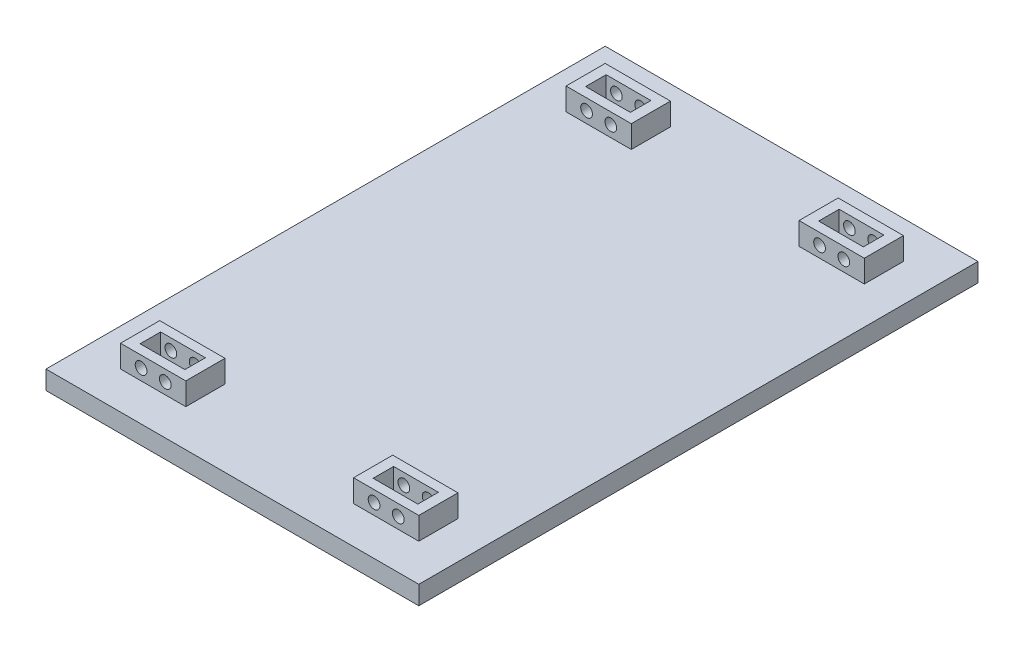
SolidWorks part; units mm, degrees
ref_plane "Front Plane" through (0, 0, 0) normal (0, 0, 1) x (1, 0, 0)
ref_plane "Top Plane" through (0, 0, 0) normal (0, 1, 0) x (1, 0, 0)
ref_plane "Right Plane" through (0, 0, 0) normal (1, 0, 0) x (0, 0, -1)
sketch "Sketch1" plane through (0, 0, 0) normal (0, 1, 0) x (1, 0, 0)
  line L1 (-16.8996, -5.3819) -> (183.1004, -5.3819)
  line L2 (-16.8996, -5.3819) -> (-16.8996, 294.6181)
  line L3 (-16.8996, 294.6181) -> (183.1004, 294.6181)
  line L4 (183.1004, -5.3819) -> (183.1004, 294.6181)
  dimension "D1" = 300
  dimension "D2" = 200
extrude "Boss-Extrude1" add sketch "Sketch1" along normal blind 10
sketch "Sketch2" plane through (0, 10, 0) normal (0, 1, 0) x (1, 0, 0)
  line L0 (133.6004, 269.6181) -> (133.6004, 258.6181)
  line L1 (157.6004, 258.6181) -> (133.6004, 258.6181)
  line L2 (157.6004, 269.6181) -> (157.6004, 258.6181)
  line L3 (157.6004, 269.6181) -> (133.6004, 269.6181)
  line L4 (128.1004, 274.6181) -> (128.1004, 253.6181)
  line L5 (3.1004, 274.6181) -> (38.1004, 274.6181)
  line L6 (3.1004, 274.6181) -> (3.1004, 253.6181)
  line L7 (3.1004, 253.6181) -> (38.1004, 253.6181)
  line L8 (38.1004, 274.6181) -> (38.1004, 253.6181)
  line L9 (8.6004, 269.6181) -> (32.6004, 269.6181)
  line L10 (8.6004, 269.6181) -> (8.6004, 258.6181)
  line L11 (8.6004, 258.6181) -> (32.6004, 258.6181)
  line L12 (32.6004, 269.6181) -> (32.6004, 258.6181)
  line L13 (83.1004, 294.6181) -> (83.1004, -5.3819)
  line L14 (183.1004, 294.6181) -> (-16.8996, 294.6181) construction
  line L15 (-16.8996, -5.3819) -> (183.1004, -5.3819) construction
  line L16 (-16.8996, 144.6181) -> (183.1004, 144.6181)
  line L17 (-16.8996, 294.6181) -> (-16.8996, -5.3819) construction
  line L18 (183.1004, -5.3819) -> (183.1004, 294.6181) construction
  line L19 (163.1004, 253.6181) -> (128.1004, 253.6181)
  line L20 (163.1004, 274.6181) -> (163.1004, 253.6181)
  line L21 (163.1004, 274.6181) -> (128.1004, 274.6181)
  line L22 (163.1004, 14.6181) -> (128.1004, 14.6181)
  line L23 (163.1004, 14.6181) -> (163.1004, 35.6181)
  line L24 (163.1004, 35.6181) -> (128.1004, 35.6181)
  line L25 (32.6004, 19.6181) -> (32.6004, 30.6181)
  line L26 (8.6004, 30.6181) -> (32.6004, 30.6181)
  line L27 (8.6004, 19.6181) -> (8.6004, 30.6181)
  line L28 (8.6004, 19.6181) -> (32.6004, 19.6181)
  line L29 (38.1004, 14.6181) -> (38.1004, 35.6181)
  line L30 (3.1004, 35.6181) -> (38.1004, 35.6181)
  line L31 (3.1004, 14.6181) -> (3.1004, 35.6181)
  line L32 (3.1004, 14.6181) -> (38.1004, 14.6181)
  line L33 (128.1004, 14.6181) -> (128.1004, 35.6181)
  line L34 (157.6004, 19.6181) -> (133.6004, 19.6181)
  line L35 (157.6004, 19.6181) -> (157.6004, 30.6181)
  line L36 (157.6004, 30.6181) -> (133.6004, 30.6181)
  line L37 (133.6004, 19.6181) -> (133.6004, 30.6181)
  dimension "D3" = 21
  dimension "D4" = 35
  dimension "D5" = 24
  dimension "D6" = 11
  dimension "D8" = 5.5
extrude "Boss-Extrude2" add sketch "Sketch2" along normal blind 12 contours L31 L32 L29 L30 L28 L27 L26 L25 | L33 L22 L23 L24 L34 L37 L36 L35 | L20 L21 L4 L19 L3 L2 L1 L0 | L8 L5 L6 L7 L9 L12 L11 L10
sketch "Sketch3" plane through (0, 0, 5.3819) normal (0, 0, 1) x (1, 0, 0)
  line L1 (-16.8996, 10) -> (183.1004, 10) construction
  line L8 (83.1004, 10) -> (83.1004, 45.2221)
  circle A0 centre (14.1004, 16) radius 3.14
  circle A1 centre (27.1004, 16) radius 3.14
  circle A2 centre (139.1004, 16) radius 3.14
  circle A3 centre (152.1004, 16) radius 3.14
extrude "Cut-Extrude1" cut sketch "Sketch3" against normal blind 1200 contours A0 | A1 | A3 | A2
